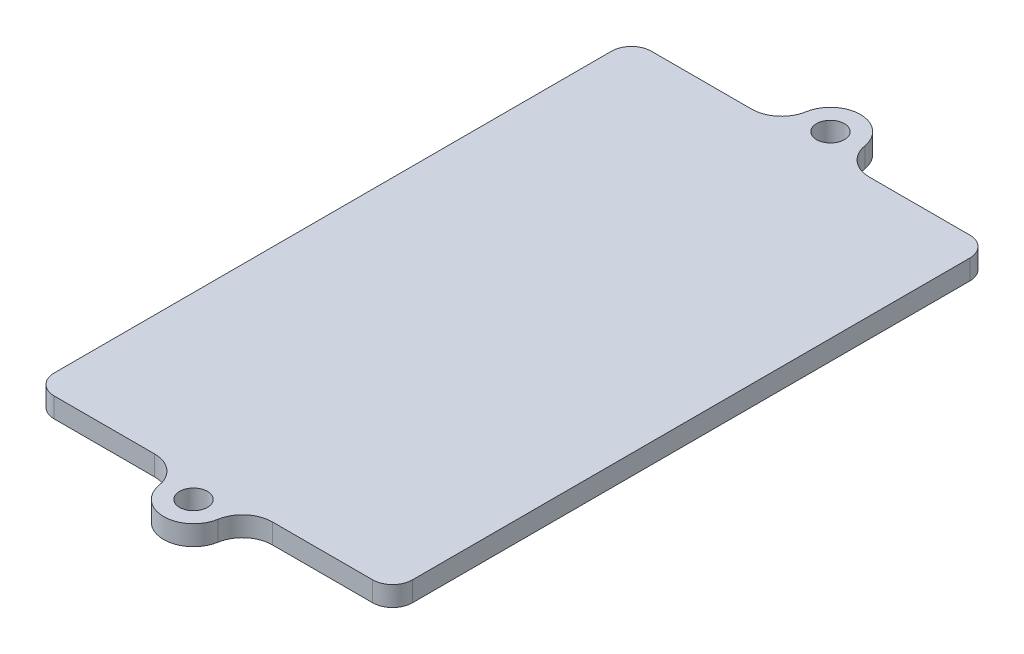
SolidWorks part; units mm, degrees
ref_plane "前视基准面" through (0, 0, 0) normal (0, 0, 1) x (1, 0, 0)
ref_plane "上视基准面" through (0, 0, 0) normal (0, 1, 0) x (1, 0, 0)
ref_plane "右视基准面" through (0, 0, 0) normal (1, 0, 0) x (0, 0, -1)
sketch "草图1" plane through (0, 0, 0) normal (0, 1, 0) x (1, 0, 0)
  line L1 (-18, 30) -> (18, 30)
  line L2 (-18, 30) -> (-18, -30)
  line L3 (-18, -30) -> (18, -30)
  line L4 (18, 30) -> (18, -30)
  dimension "D1" = 60
  dimension "D2" = 36
  dimension "D3" = 18
  dimension "D4" = 30
extrude "凸台-拉伸1" add sketch "草图1" along normal blind 2
fillet "圆角1" radius 2 4 edges at (-18, 1, 30) (18, 1, 30) (18, 1, -30) (-18, 1, -30)
sketch "草图2" plane through (0, 2, 0) normal (0, 1, 0) x (1, 0, 0)
  line L0 (16, 30) -> (-16, 30) construction
  line L1 (-35.4453, 0) -> (31.68, 0) construction
  circle A0 centre (0, 32) radius 3
  circle A1 centre (0, 32) radius 3
  circle A2 centre (0, 32) radius 1.4
  circle A3 centre (0, -32) radius 1.4
  circle A4 centre (0, -32) radius 3
  line M6 (-16, -30) -> (16, -30)
  line M10 (16, 30) -> (-16, 30)
  dimension "D1" = 2
extrude "凸台-拉伸2" add sketch "草图2" against normal blind 2 contours A0 A2 M10 | A4 A3 M6
fillet "圆角2" radius 3 4 edges at (-2.2361, 1, 30) (2.2361, 1, 30) (2.2361, 1, -30) (-2.2361, 1, -30)
